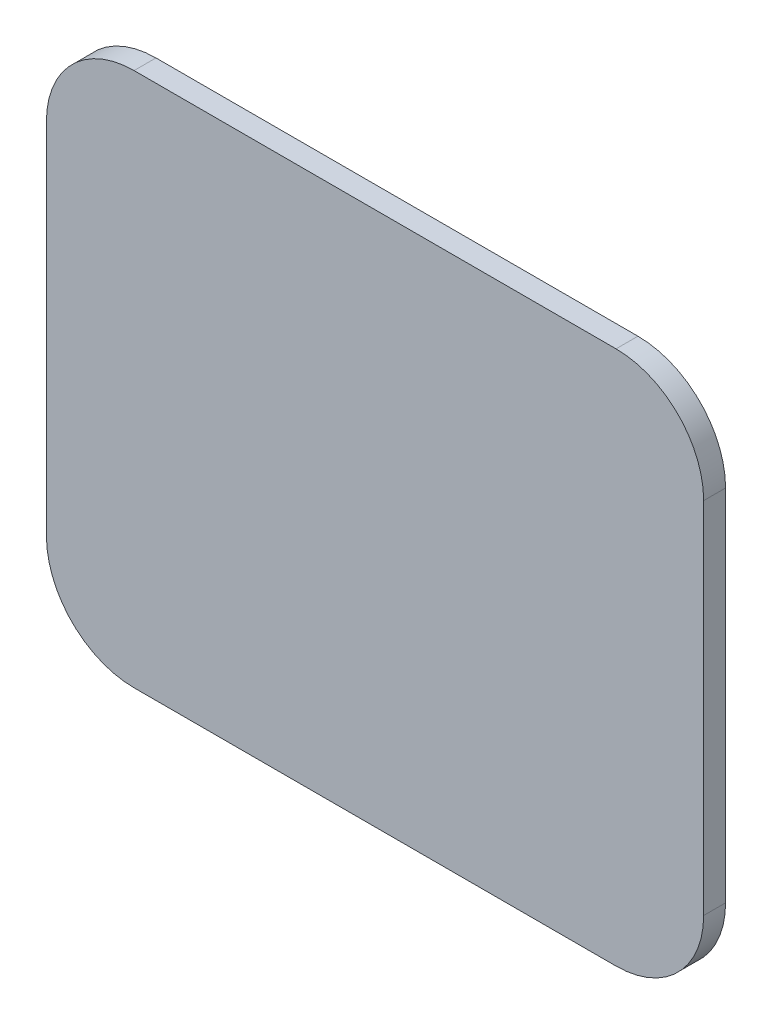
SolidWorks part; units mm, degrees
ref_plane "前视基准面" through (0, 0, 0) normal (0, 0, 1) x (1, 0, 0)
ref_plane "上视基准面" through (0, 0, 0) normal (0, 1, 0) x (1, 0, 0)
ref_plane "右视基准面" through (0, 0, 0) normal (1, 0, 0) x (0, 0, -1)
other "Configuration Table"
sketch "草图1" plane through (0, 0, 0) normal (0, 0, 1) x (1, 0, 0)
  line L1 (-55, -61) -> (55, -61)
  line L2 (-75, -41) -> (-75, 41)
  line L3 (-55, 61) -> (55, 61)
  line L4 (75, -41) -> (75, 41)
  line L5 (-75, -61) -> (75, 61) construction
  line L6 (-75, 61) -> (75, -61) construction
  arc A0 (55, 61) -> (75, 41) centre (55, 41) cw
  arc A1 (55, -61) -> (75, -41) centre (55, -41) ccw
  arc A2 (-55, -61) -> (-75, -41) centre (-55, -41) cw
  arc A3 (-75, 41) -> (-55, 61) centre (-55, 41) cw
  point P0 (0, 0)
  dimension "D3" = 20
  dimension "D1" = 150
  dimension "D2" = 122
extrude "凸台-拉伸1" add sketch "草图1" along normal blind 5
